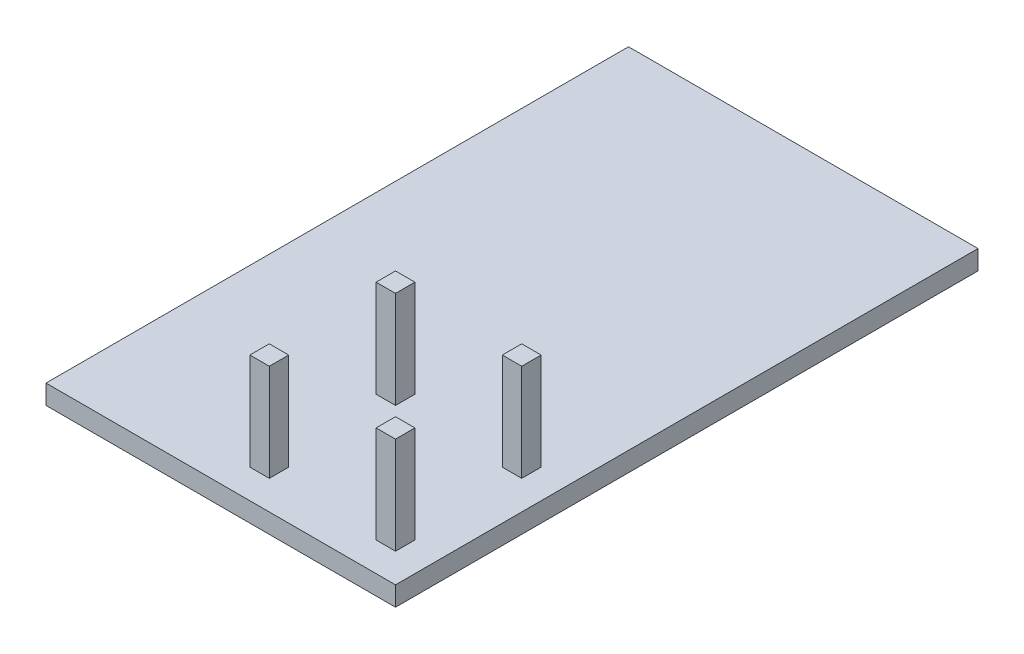
SolidWorks part; units mm, degrees
material "Pine"
ref_plane "Front Plane" through (0, 0, 0) normal (0, 0, 1) x (1, 0, 0)
ref_plane "Top Plane" through (0, 0, 0) normal (0, 1, 0) x (1, 0, 0)
ref_plane "Right Plane" through (0, 0, 0) normal (1, 0, 0) x (0, 0, -1)
sketch "Sketch3" plane through (0, 0, 0) normal (0, 1, 0) x (1, 0, 0)
  line L1 (-90, -150) -> (90, -150)
  line L2 (-90, -150) -> (-90, 150)
  line L3 (-90, 150) -> (90, 150)
  line L4 (90, -150) -> (90, 150)
  line L5 (-90, -150) -> (90, 150) construction
  line L6 (-90, 150) -> (90, -150) construction
  point P0 (0, 0)
  dimension "D1" = 180
  dimension "D2" = 300
extrude "Boss-Extrude1" add sketch "Sketch3" along normal blind 10
sketch "Sketch4" plane through (0, 10, 0) normal (0, 1, 0) x (1, 0, 0)
  line L0 (90, -150) -> (90, 150) construction
  line L1 (75, -135) -> (65, -135)
  line L2 (75, -135) -> (75, -125)
  line L3 (75, -60) -> (65, -60)
  line L4 (0, -135) -> (0, -125)
  line L5 (-90, -150) -> (90, -150) construction
  line L6 (10, -135) -> (10, -125)
  line L7 (65, -60) -> (65, -70)
  line L8 (10, -60) -> (0, -60)
  line L9 (10, -135) -> (0, -135)
  line L10 (0, -125) -> (10, -125)
  line L11 (0, -70) -> (10, -70)
  line L12 (65, -70) -> (75, -70)
  line L13 (65, -125) -> (75, -125)
  line L14 (0, -70) -> (0, -60)
  line L15 (10, -70) -> (10, -60)
  line L16 (65, -125) -> (65, -135)
  line L17 (75, -70) -> (75, -60)
  point P20 (70, -125)
  dimension "D1" = 15
  dimension "D2" = 15
  dimension "D3" = 75
  dimension "D4" = 75
  dimension "D5" = 10
  dimension "D6" = 10
  dimension "D7" = 10
  dimension "D8" = 10
  dimension "D9" = 10
extrude "Boss-Extrude2" add sketch "Sketch4" along normal blind 50
